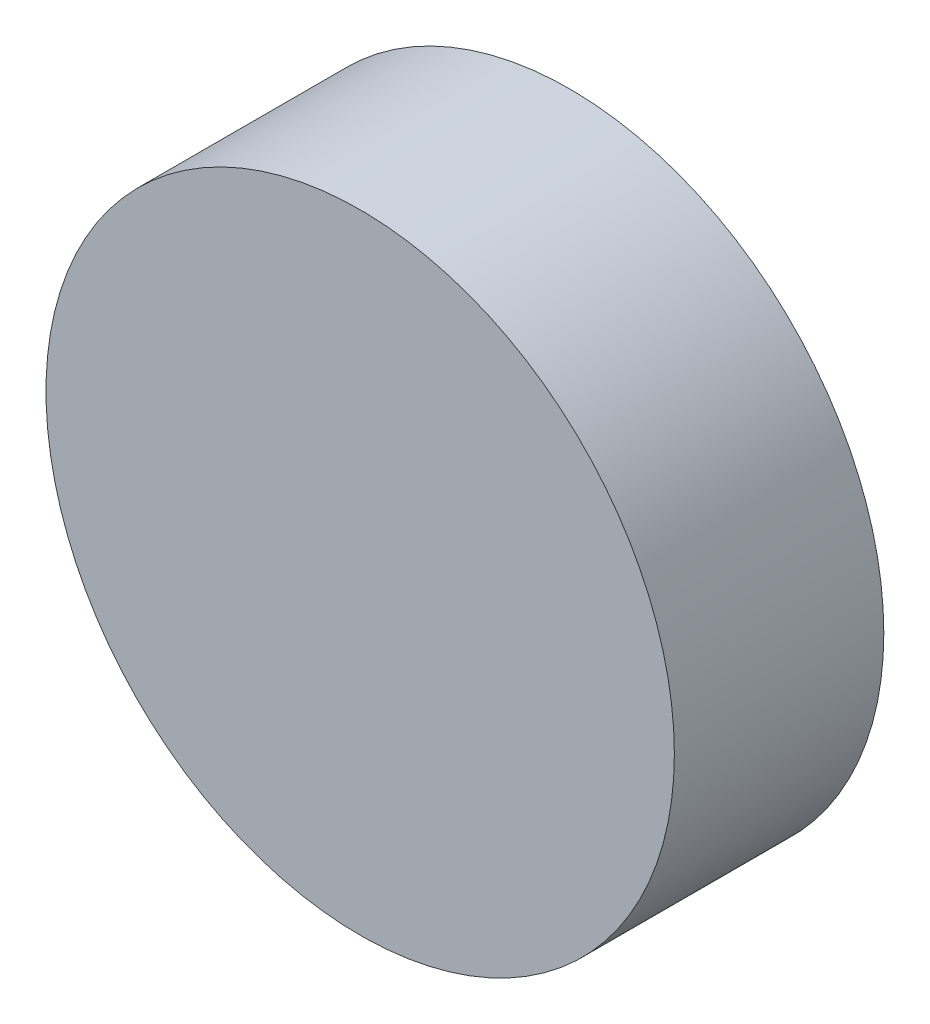
SolidWorks part; units mm, degrees
ref_plane "Alzado" through (0, 0, 0) normal (0, 0, 1) x (1, 0, 0)
ref_plane "Planta" through (0, 0, 0) normal (0, 1, 0) x (1, 0, 0)
ref_plane "Vista lateral" through (0, 0, 0) normal (1, 0, 0) x (0, 0, -1)
sketch "Croquis1" plane through (0, 0, 0) normal (0, 0, 1) x (1, 0, 0)
  circle A0 centre (0, 0) radius 3
  dimension "D1" = 6
extrude "Saliente-Extruir1" add sketch "Croquis1" along normal blind 2
